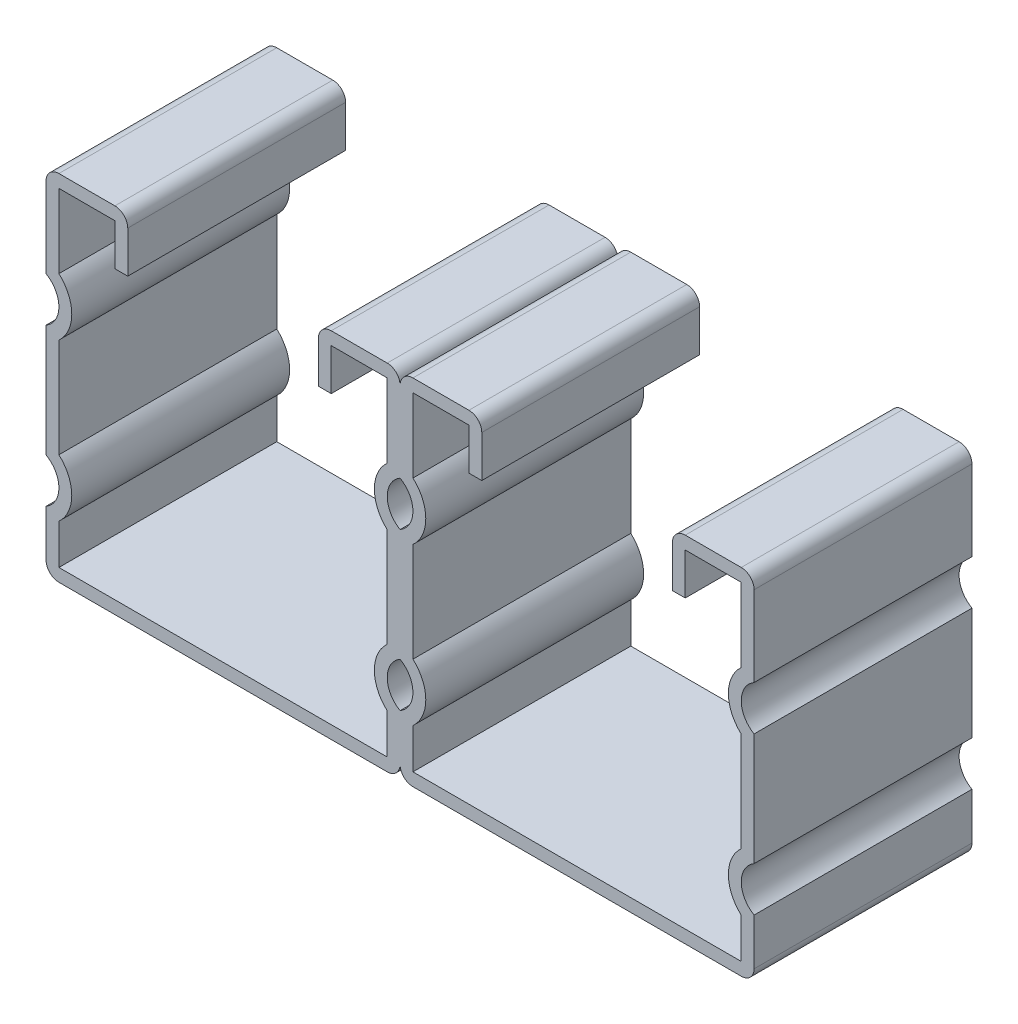
SolidWorks part; units mm, degrees
ref_plane "Plane1" through (0, 0, 0) normal (0, 0, 1) x (1, 0, 0)
ref_plane "Plane2" through (0, 0, 0) normal (0, 1, 0) x (1, 0, 0)
ref_plane "Plane3" through (0, 0, 0) normal (1, 0, 0) x (0, 0, -1)
sketch "Sketch1" plane through (0, 0, 0) normal (0, 0, 1) x (1, 0, 0)
  line L0 (-20.6375, 21.1074) -> (-20.6375, 11.7397)
  line L1 (-20.6375, 6.5483) -> (-20.6375, -6.5483)
  line L2 (-19.1389, -18.669) -> (19.1389, -18.669)
  line L3 (20.6375, -17.1704) -> (20.6375, -11.7397)
  line L4 (20.6375, 11.7397) -> (20.6375, 21.1074)
  line L5 (19.1389, 22.606) -> (12.6111, 22.606)
  line L6 (11.1125, 21.1074) -> (11.1125, 16.256)
  line L7 (-19.1389, 22.606) -> (-12.6111, 22.606)
  line L8 (-11.1125, 21.1074) -> (-11.1125, 16.256)
  line L9 (19.1389, -12.495) -> (19.1389, 12.495) construction
  line L10 (-19.1389, 12.495) -> (-19.1389, -12.495) construction
  line L11 (-12.6111, 21.1074) -> (-12.6111, 16.256)
  line L12 (-19.1389, 21.1074) -> (-12.6111, 21.1074)
  line L13 (-19.1389, 21.1074) -> (-19.1389, 12.495)
  line L14 (-19.1389, 5.793) -> (-19.1389, -5.793)
  line L15 (-19.1389, -17.1704) -> (19.1389, -17.1704)
  line L16 (19.1389, -17.1704) -> (19.1389, -12.495)
  line L17 (19.1389, 12.495) -> (19.1389, 21.1074)
  line L18 (19.1389, 21.1074) -> (12.6111, 21.1074)
  line L19 (12.6111, 21.1074) -> (12.6111, 16.256)
  line L20 (-12.6111, 16.256) -> (-11.1125, 16.256)
  line L21 (11.1125, 16.256) -> (12.6111, 16.256)
  line L22 (-10.16, 0) -> (12.7, 0) construction
  line L23 (-20.6375, -11.7397) -> (-20.6375, -17.1704)
  line L24 (-19.1389, -12.495) -> (-19.1389, -17.1704)
  line L25 (20.6375, -6.5483) -> (20.6375, 6.5483)
  line L26 (19.1389, -5.793) -> (19.1389, 5.793)
  arc A0 (20.6375, 11.7397) -> (20.6375, 6.5483) centre (22.1361, 9.144) ccw
  arc A1 (-20.6375, 6.5483) -> (-20.6375, 11.7397) centre (-22.1361, 9.144) ccw
  arc A2 (-12.6111, 22.606) -> (-11.1125, 21.1074) centre (-12.6111, 21.1074) cw
  arc A3 (-20.6375, 21.1074) -> (-19.1389, 22.606) centre (-19.1389, 21.1074) cw
  arc A4 (-19.1389, -18.669) -> (-20.6375, -17.1704) centre (-19.1389, -17.1704) cw
  arc A5 (20.6375, -17.1704) -> (19.1389, -18.669) centre (19.1389, -17.1704) cw
  arc A6 (19.1389, 22.606) -> (20.6375, 21.1074) centre (19.1389, 21.1074) cw
  arc A7 (11.1125, 21.1074) -> (12.6111, 22.606) centre (12.6111, 21.1074) cw
  arc A8 (-19.1389, 5.793) -> (-19.1389, 12.495) centre (-22.1361, 9.144) ccw
  arc A9 (19.1389, 12.495) -> (19.1389, 5.793) centre (22.1361, 9.144) ccw
  arc A10 (20.6375, -11.7397) -> (20.6375, -6.5483) centre (22.1361, -9.144) cw
  arc A11 (19.1389, -12.495) -> (19.1389, -5.793) centre (22.1361, -9.144) cw
  arc A12 (-19.1389, -5.793) -> (-19.1389, -12.495) centre (-22.1361, -9.144) cw
  arc A13 (-20.6375, -6.5483) -> (-20.6375, -11.7397) centre (-22.1361, -9.144) cw
  dimension "D9" = 2.9972
  dimension "D10" = 2.9972
  dimension "D1" = 20.6375
  dimension "Width" = 41.275
  dimension "base" = 18.669
  dimension "ToeHt" = 22.606
  dimension "D6" = 22.225
  dimension "edge" = 9.525
  dimension "Lip" = 6.35
  dimension "D2" = 9.525
  dimension "gauge" = 1.4986
extrude "Base-Extrude" add sketch "Sketch1" along normal mid plane 25.4
pattern_linear "LPattern1" count 2 spacing 41.275 along (1, 0, 0) of "Base-Extrude"
equation "\"D1@Sketch1\" = \"Width@Sketch1\" / 2"
equation "\"D6@Sketch1\" = \"Width@Sketch1\" - 2 * \"edge@Sketch1\""
equation "\"D10@Sketch1\" = 2 * \"gauge@Sketch1\""
equation "\"D9@Sketch1\" = \"D10@Sketch1\""
equation "\"D2@Sketch1\" = \"edge@Sketch1\""
